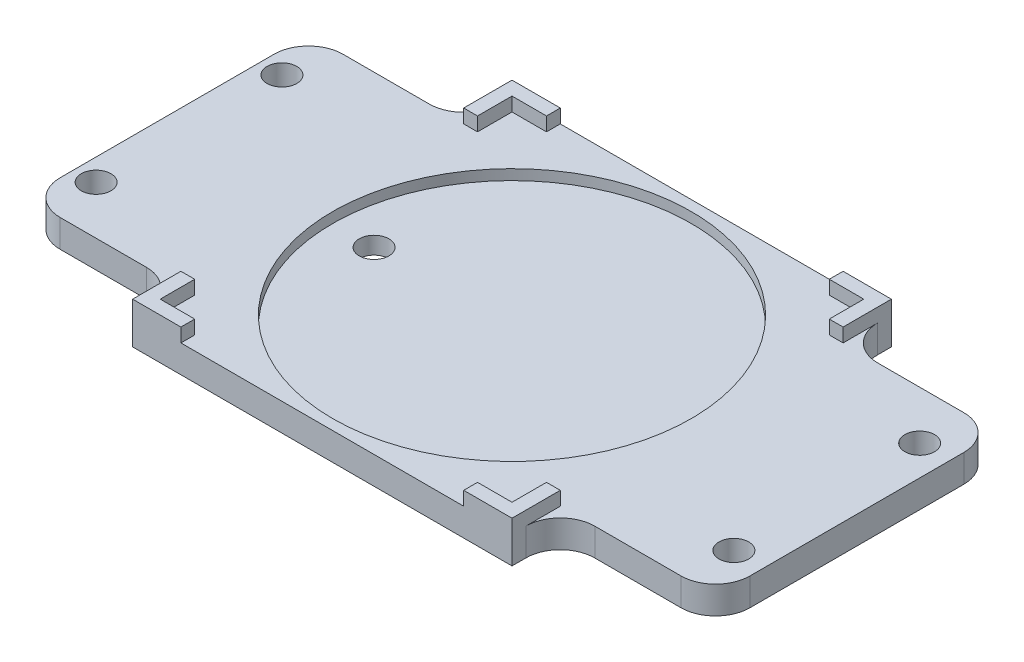
SolidWorks part; units mm, degrees
material "ABS"
ref_plane "Front Plane" through (0, 0, 0) normal (0, 0, 1) x (1, 0, 0)
ref_plane "Top Plane" through (0, 0, 0) normal (0, 1, 0) x (1, 0, 0)
ref_plane "Right Plane" through (0, 0, 0) normal (1, 0, 0) x (0, 0, -1)
sketch "Sketch1" plane through (0, 0, 0) normal (0, 1, 0) x (1, 0, 0)
  line L1 (-50, 27.5) -> (50, 27.5)
  line L2 (-50, 27.5) -> (-50, -27.5)
  line L3 (-50, -27.5) -> (50, -27.5)
  line L4 (50, 27.5) -> (50, -27.5)
  line L5 (-50, 27.5) -> (50, -27.5) construction
  line L6 (-50, -27.5) -> (50, 27.5) construction
  point P0 (0, 0)
  dimension "D1" = 55
  dimension "D2" = 100
extrude "Boss-Extrude1" add sketch "Sketch1" along normal blind 4
hole_wizard "#6 Clearance Hole1" positions "Sketch2" profile "Sketch3" hole size "#6" standard "ANSI Inch" end condition through all
sketch "Sketch2" plane through (0, 4, 0) normal (0, 1, 0) x (1, 0, 0)
  arc A0 (45.6352, 12.1178) -> (45.6352, 14.8229) centre (45.6352, 13.4704) ccw construction
  arc A1 (45.6352, -14.8229) -> (45.6352, -12.1178) centre (45.6352, -13.4704) ccw construction
  arc A2 (-46.825, 14.8229) -> (-46.825, 12.1178) centre (-46.825, 13.4704) ccw construction
  arc A3 (-46.825, -12.1178) -> (-46.825, -14.8229) centre (-46.825, -13.4704) ccw construction
  point P0 (45.6352, 13.4704)
  point P2 (45.6352, -13.4704)
  point P4 (-46.825, -13.4704)
  point P6 (-46.825, 13.4704)
  point P23 (-20, 0)
  dimension "D1" = 20
sketch "Sketch3" plane through (45.6352, 4, -13.4704) normal (1, 0, 0) x (0, 0, 1)
  line L0 (0, 0) -> (0, 4)
  line L1 (0, 4) -> (2.1526, 4)
  line L2 (2.1526, 4) -> (2.1526, 0)
  line L5 (2.1526, 0) -> (0, 0)
  line L11 (0, -6.35) -> (0, 107.95) construction
  dimension "Thru Hole Dia." = 4.3053
  dimension "Thru Hole Depth" = 4
sketch "Sketch4" plane through (0, 4, 0) normal (0, 1, 0) x (1, 0, 0)
  circle A0 centre (0, 0) radius 26
  dimension "D1" = 52
extrude "Cut-Extrude1" cut sketch "Sketch4" against normal blind 1.5
sketch "Sketch6" plane through (0, 4, 0) normal (0, 1, 0) x (1, 0, 0)
  line L0 (-20.5, 25.5) -> (-20.5, 27.5)
  line L2 (50, 27.5) -> (-50, 27.5) construction
  line L3 (-20.5, 27.5) -> (-27.5, 27.5)
  line L4 (-27.5, 27.5) -> (-27.5, 20.5)
  line L5 (-27.5, 20.5) -> (-25.5, 20.5)
  line L7 (-25.5, 20.5) -> (-25.5, 25.5)
  line L8 (-25.5, 25.5) -> (-20.5, 25.5)
  dimension "D1" = 5
extrude "Boss-Extrude2" add sketch "Sketch6" along normal blind 2
sketch "Sketch7" plane through (0, 4, 0) normal (0, 1, 0) x (1, 0, 0)
  line L1 (-50, 27.5) -> (-27.5, 27.5)
  line L2 (-50, 27.5) -> (-50, 20.5)
  line L3 (-50, 20.5) -> (-27.5, 20.5)
  line L4 (-27.5, 27.5) -> (-27.5, 20.5)
extrude "Cut-Extrude2" cut sketch "Sketch7" against normal up to next
mirror "Mirror1" about plane through (0, 0, 0) normal (0, 0, 1) of "Boss-Extrude2", "Cut-Extrude2"
mirror "Mirror2" about plane through (0, 0, 0) normal (1, 0, 0) of "Mirror1", "Boss-Extrude2", "Cut-Extrude2"
fillet "Fillet1" radius 5 8 edges at (-50, 2, -20.5) (-27.5, 2, -20.5) (50, 2, -20.5) (27.5, 2, -20.5) (50, 2, 20.5) (27.5, 2, 20.5) (-27.5, 2, 20.5) (-50, 2, 20.5)
equation "\"1é5\"=2"
